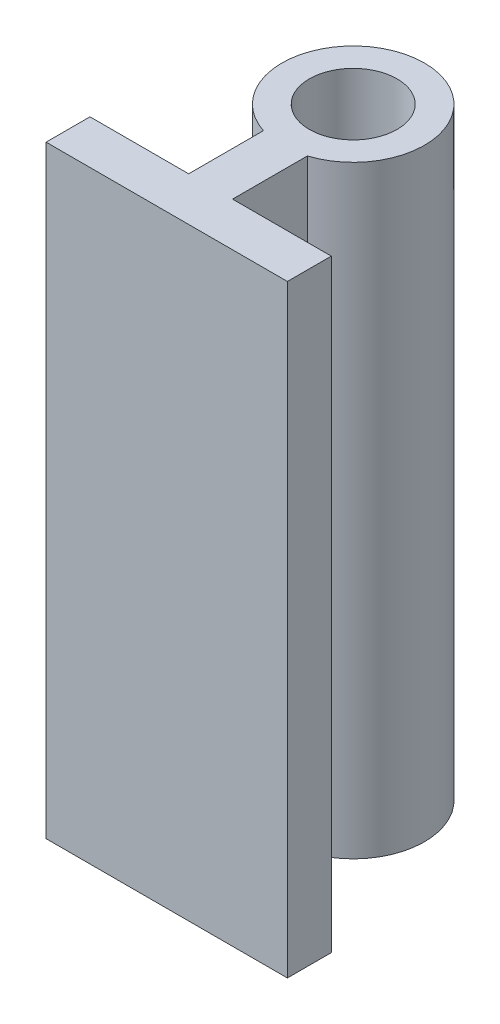
SolidWorks part; units mm, degrees
ref_plane "Спереди" through (0, 0, 0) normal (0, 0, 1) x (1, 0, 0)
ref_plane "Сверху" through (0, 0, 0) normal (0, 1, 0) x (1, 0, 0)
ref_plane "Справа" through (0, 0, 0) normal (1, 0, 0) x (0, 0, -1)
sketch "Эскиз1" plane through (0, 0, 0) normal (0, 1, 0) x (1, 0, 0)
  line L0 (0, 6.5) -> (0, 4)
  line L1 (0, 0) -> (2, 0)
  line L2 (0, 0) -> (0, -17)
  line L3 (0, -17) -> (2, -17)
  line L4 (2, 0) -> (2, -17)
  line L5 (2, -17) -> (11, -17)
  line L6 (2, -17) -> (2, -13)
  line L7 (2, -13) -> (11, -13)
  line L8 (11, -17) -> (11, -13)
  circle A0 centre (0, 0) radius 4
  circle A1 centre (0, 0) radius 6.5
  dimension "D1" = 8
  dimension "D2" = 13
  dimension "D3" = 11
  dimension "D4" = 17
  dimension "D5" = 2
  dimension "D6" = 4
extrude "Бобышка-Вытянуть1" add sketch "Эскиз1" along normal blind 55 contours L4 A1 L0 A0 | L2 A1 L4 A0 | A1 L2 L3 L4 | L5 L8 L7 L4
mirror "Зеркальное отражение1" about plane through (0, 55, 0) normal (1, 0, 0) of bodies 105
